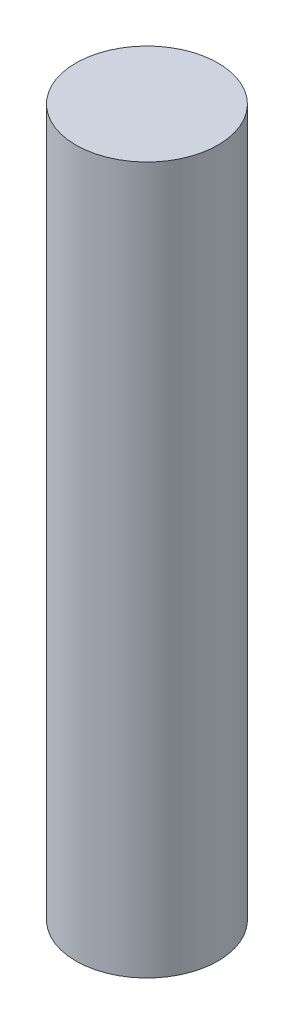
SolidWorks part; units mm, degrees
ref_plane "Alzado" through (0, 0, 0) normal (0, 0, 1) x (1, 0, 0)
ref_plane "Planta" through (0, 0, 0) normal (0, 1, 0) x (1, 0, 0)
ref_plane "Vista lateral" through (0, 0, 0) normal (1, 0, 0) x (0, 0, -1)
sketch "Croquis1" plane through (0, 0, 0) normal (0, 1, 0) x (1, 0, 0)
  circle A0 centre (0, 0) radius 4
  dimension "D1" = 8
extrude "Saliente-Extruir1" add sketch "Croquis1" along normal up to vertex (39.769 mm away)
